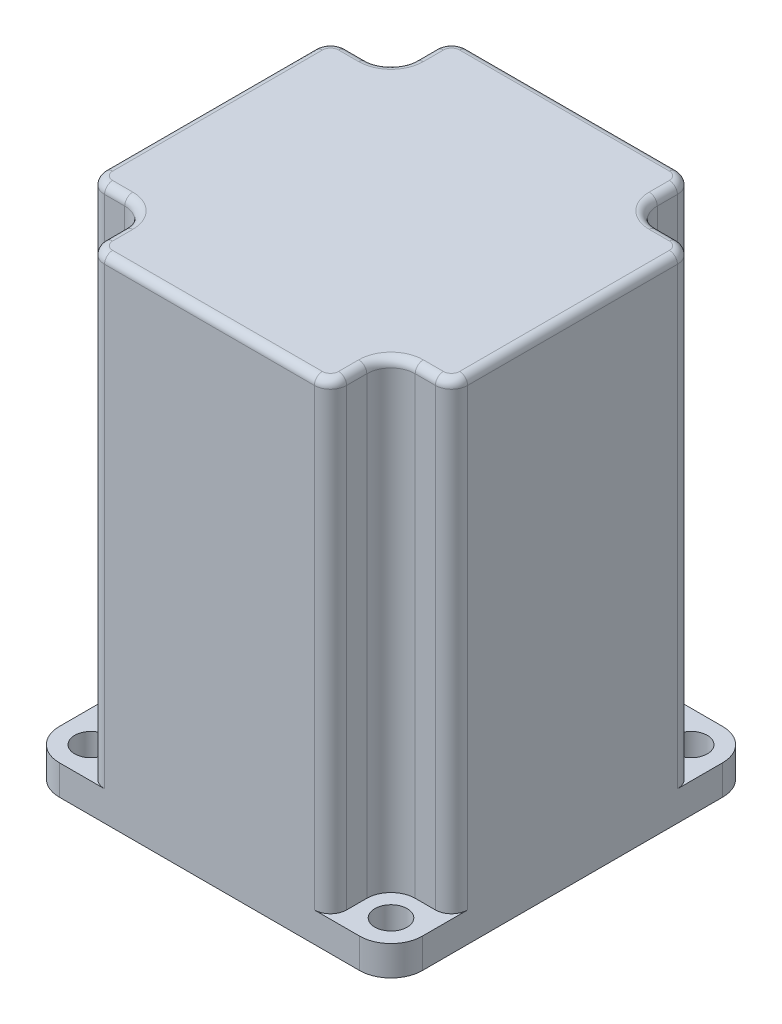
SolidWorks part; units mm, degrees
material "Plain Carbon Steel"
ref_plane "Front Plane" through (0, 0, 0) normal (0, 0, 1) x (1, 0, 0)
ref_plane "Top Plane" through (0, 0, 0) normal (0, 1, 0) x (1, 0, 0)
ref_plane "Right Plane" through (0, 0, 0) normal (1, 0, 0) x (0, 0, -1)
sketch "Sketch1" plane through (0, 0, 0) normal (0, 1, 0) x (1, 0, 0)
  line L0 (0, 28.575) -> (0, -28.575) construction
  line L1 (-23.622, 28.575) -> (23.622, 28.575)
  line L2 (-28.575, 23.622) -> (-28.575, -23.622)
  line L3 (-23.622, -28.575) -> (23.622, -28.575)
  line L4 (28.575, 23.622) -> (28.575, -23.622)
  line L6 (23.622, -23.622) -> (-23.622, -23.622) construction
  line L7 (23.622, -23.622) -> (23.622, 23.622) construction
  line L8 (23.622, 23.622) -> (-23.622, 23.622) construction
  line L9 (-23.622, -23.622) -> (-23.622, 23.622) construction
  line L11 (23.622, 23.622) -> (-23.622, -23.622) construction
  circle A0 centre (-23.622, 23.622) radius 2.54
  circle A1 centre (23.622, 23.622) radius 2.54
  circle A2 centre (23.622, -23.622) radius 2.54
  circle A3 centre (-23.622, -23.622) radius 2.54
  arc A4 (-28.575, -23.622) -> (-23.622, -28.575) centre (-23.622, -23.622) ccw
  arc A5 (23.622, -28.575) -> (28.575, -23.622) centre (23.622, -23.622) ccw
  arc A6 (23.622, 28.575) -> (28.575, 23.622) centre (23.622, 23.622) cw
  arc A7 (-23.622, 28.575) -> (-28.575, 23.622) centre (-23.622, 23.622) ccw
  point P6 (0, 0)
  dimension "D3" = 5.08
  dimension "D1" = 57.15
  dimension "D2" = 47.244
extrude "Boss-Extrude1" add sketch "Sketch1" along normal blind 4.699
sketch "Sketch2" plane through (0, 4.699, 0) normal (0, 1, 0) x (1, 0, 0)
  line L0 (-19.05, -28.575) -> (-19.05, -19.05)
  line L1 (-23.622, -28.575) -> (23.622, -28.575) construction
  line L2 (-19.05, -19.05) -> (-28.575, -19.05)
  line L3 (-28.575, 23.622) -> (-28.575, -23.622) construction
  line L4 (-28.575, -19.05) -> (-28.575, 19.05)
  line L5 (-28.575, 19.05) -> (-19.05, 19.05)
  line L6 (-19.05, 19.05) -> (-19.05, 28.575)
  line L7 (23.622, 28.575) -> (-23.622, 28.575) construction
  line L8 (-19.05, 28.575) -> (19.05, 28.575)
  line L9 (19.05, 28.575) -> (19.05, 19.05)
  line L10 (19.05, 19.05) -> (28.575, 19.05)
  line L11 (28.575, -23.622) -> (28.575, 23.622) construction
  line L12 (28.575, 19.05) -> (28.575, -19.05)
  line L13 (28.575, -19.05) -> (19.05, -19.05)
  line L14 (19.05, -19.05) -> (19.05, -28.575)
  line L15 (19.05, -28.575) -> (-19.05, -28.575)
  dimension "D1" = 38.1
extrude "Boss-Extrude2" add sketch "Sketch2" along normal blind 72.771
fillet "Fillet1" radius 3.81 4 edges at (-19.05, 41.0845, 19.05) (-19.05, 41.0845, -19.05) (19.05, 41.0845, -19.05) (19.05, 41.0845, 19.05)
fillet "Fillet2" radius 2.54 8 edges
fillet "Fillet3" radius 1.27 24 edges at (27.8311, 77.47, 18.3061) (24.4475, 77.47, 19.05) (20.1659, 77.47, 20.1659) (19.05, 77.47, 24.4475) (18.3061, 77.47, 27.8311) (0, 77.47, 28.575) (-18.3061, 77.47, 27.8311) (-19.05, 77.47, 24.4475) (-20.1659, 77.47, 20.1659) (-24.4475, 77.47, 19.05) (-27.8311, 77.47, 18.3061) (-28.575, 77.47, 0) (-27.8311, 77.47, -18.3061) (-24.4475, 77.47, -19.05) (-20.1659, 77.47, -20.1659) (-19.05, 77.47, -24.4475) (-18.3061, 77.47, -27.8311) (0, 77.47, -28.575) (18.3061, 77.47, -27.8311) (19.05, 77.47, -24.4475) (20.1659, 77.47, -20.1659) (24.4475, 77.47, -19.05) (27.8311, 77.47, -18.3061) (28.575, 77.47, 0)
sketch "Sketch3" plane through (0, 0, 0) normal (0, -1, 0) x (1, 0, 0)
  circle A0 centre (0, 0) radius 19.05
  dimension "D1" = 38.1
extrude "Boss-Extrude3" add sketch "Sketch3" along normal blind 1.524
sketch "Sketch4" plane through (0, -1.524, 0) normal (0, -1, 0) x (1, 0, 0)
  circle A0 centre (0, 0) radius 3.175
  dimension "D1" = 6.35
sketch "Sketch5" plane through (0, 0, 0) normal (0, -1, 0) x (1, 0, 0)
  circle A0 centre (0, 0) radius 22.225
  dimension "D1" = 44.45
extrude "Cut-Extrude1" cut sketch "Sketch5" against normal blind 66.802 from offset 6.35 offset against normal yes
extrude "Cut-Extrude4" cut sketch "Sketch4" against normal blind 12.7
